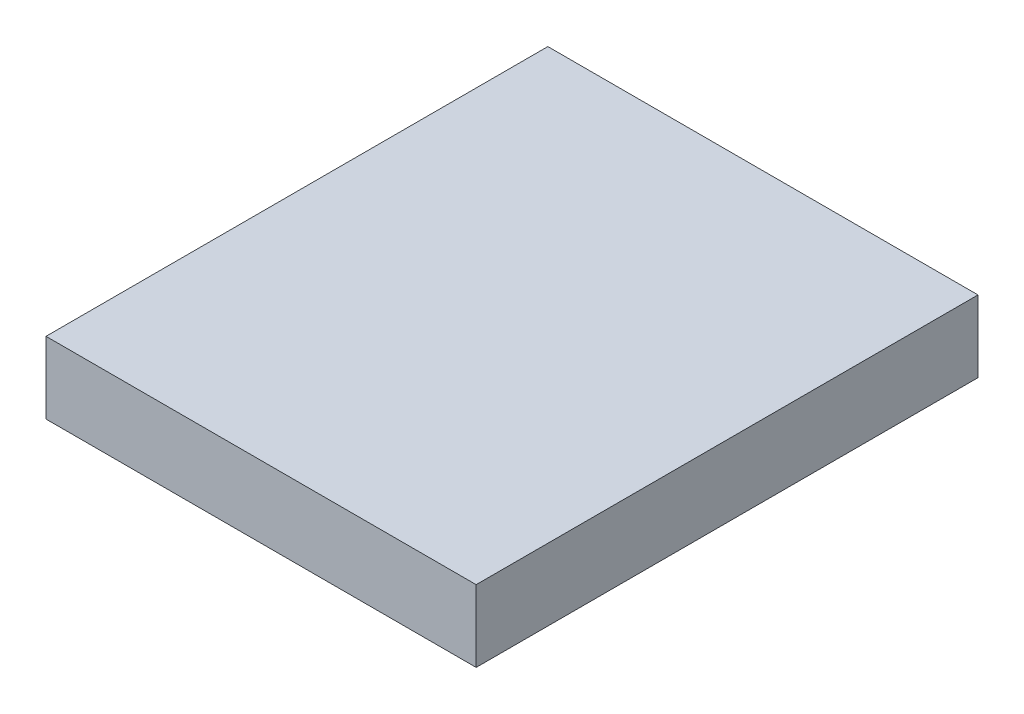
SolidWorks part; units mm, degrees
ref_plane "Front Plane" through (0, 0, 0) normal (0, 0, 1) x (1, 0, 0)
ref_plane "Top Plane" through (0, 0, 0) normal (0, 1, 0) x (1, 0, 0)
ref_plane "Right Plane" through (0, 0, 0) normal (1, 0, 0) x (0, 0, -1)
sketch "Sketch1" plane through (0, 0, 0) normal (0, 1, 0) x (1, 0, 0)
  line L1 (-15, -17.5) -> (15, -17.5)
  line L2 (-15, -17.5) -> (-15, 17.5)
  line L3 (-15, 17.5) -> (15, 17.5)
  line L4 (15, -17.5) -> (15, 17.5)
  line L5 (-15, -17.5) -> (15, 17.5) construction
  line L6 (-15, 17.5) -> (15, -17.5) construction
  point P0 (0, 0)
  dimension "D1" = 35
  dimension "D2" = 30
extrude "Boss-Extrude1" add sketch "Sketch1" along normal blind 5
